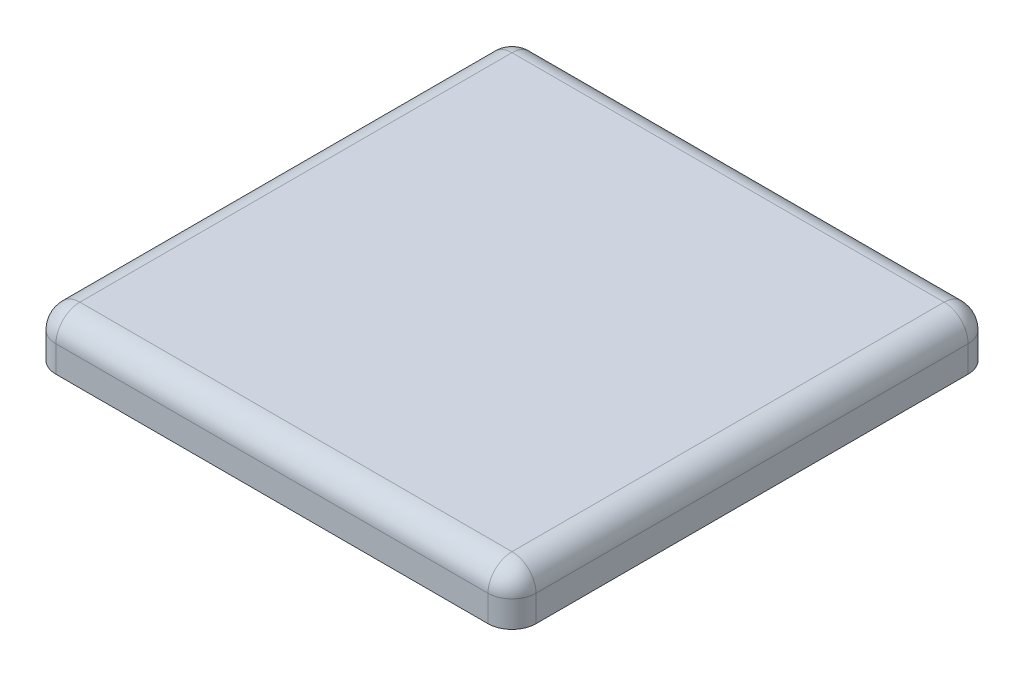
SolidWorks part; units mm, degrees
ref_plane "Ebene vorne" through (0, 0, 0) normal (0, 0, 1) x (1, 0, 0)
ref_plane "Ebene oben" through (0, 0, 0) normal (0, 1, 0) x (1, 0, 0)
ref_plane "Ebene rechts" through (0, 0, 0) normal (1, 0, 0) x (0, 0, -1)
sketch "Skizze1" plane through (0, 0, 0) normal (0, 1, 0) x (1, 0, 0)
  line L0 (0, 48.6612) -> (0, -45.6616) construction
  line L1 (-50.9943, 0) -> (53.6607, 0) construction
  line L2 (-20, -18) -> (-20, 18)
  line L3 (-18, 20) -> (18, 20)
  line L4 (20, -18) -> (20, 18)
  line L5 (-18, -20) -> (18, -20)
  arc A0 (-18, 20) -> (-20, 18) centre (-18, 18) ccw
  arc A1 (18, 20) -> (20, 18) centre (18, 18) cw
  arc A2 (18, -20) -> (20, -18) centre (18, -18) ccw
  arc A3 (-18, -20) -> (-20, -18) centre (-18, -18) cw
  point P8 (-20, 0)
  point P13 (0, 20)
  point P20 (0, -20)
  point P21 (20, 0)
  dimension "D1" = 2
  dimension "D2" = 40
extrude "Aufsatz-Linear austragen1" add sketch "Skizze1" along normal blind 4.2
fillet "Verrundung1" radius 2 8 edges at (19.4142, 4.2, 19.4142) (0, 4.2, 20) (-19.4142, 4.2, 19.4142) (-20, 4.2, 0) (-19.4142, 4.2, -19.4142) (0, 4.2, -20) (19.4142, 4.2, -19.4142) (20, 4.2, 0)
sketch "Skizze2" plane through (0, 0, 0) normal (0, -1, 0) x (1, 0, 0)
  circle A0 centre (0, 0) radius 3.5
  dimension "D1" = 7
extrude "Aufsatz-Linear austragen2" add sketch "Skizze2" along normal blind 10
chamfer "Fase1" distance 3 angle 20 1 edges at (0, -10, -3.5)
